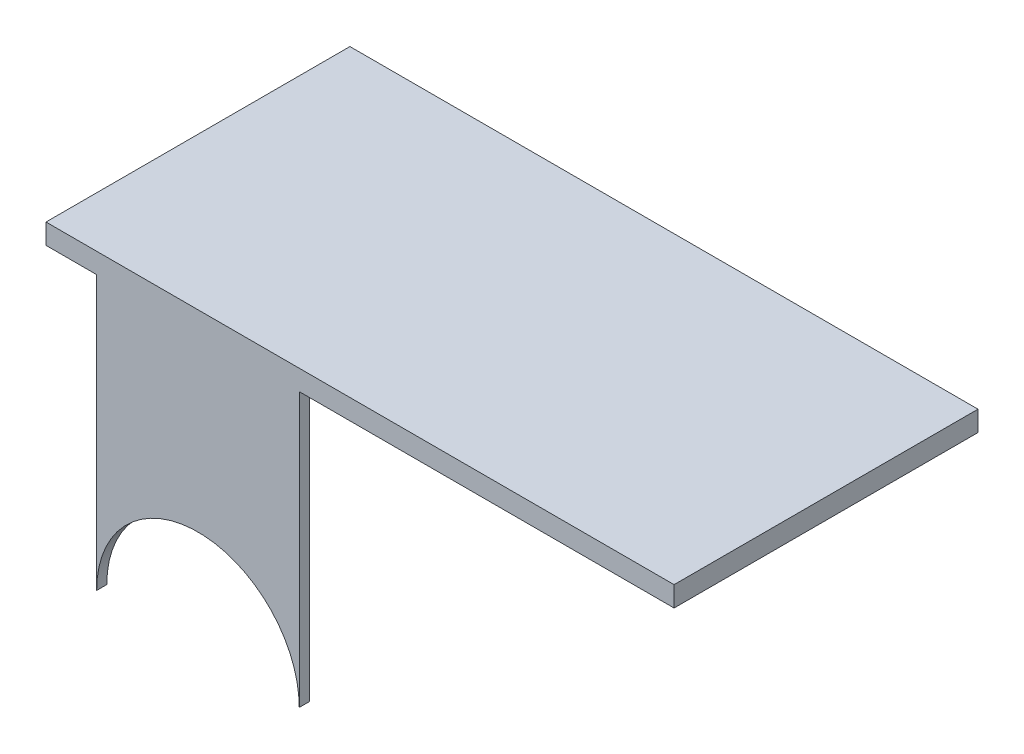
SolidWorks part; units mm, degrees
ref_plane "Front Plane" through (0, 0, 0) normal (0, 0, 1) x (1, 0, 0)
ref_plane "Top Plane" through (0, 0, 0) normal (0, 1, 0) x (1, 0, 0)
ref_plane "Right Plane" through (0, 0, 0) normal (1, 0, 0) x (0, 0, -1)
sketch "Sketch2" plane through (0, 0, 0) normal (0, 0, 1) x (1, 0, 0)
  line L0 (-44.925, -5.1312) -> (-44.925, 21.8688)
  line L1 (-44.925, 21.8688) -> (-24.925, 21.8688)
  line L2 (-24.925, 21.8688) -> (-24.925, -5.1312)
  arc A1 (-44.925, -5.1312) -> (-24.925, -5.1312) centre (-34.925, -5.1312) cw
  point P1 (0, 0)
  dimension "D1" = 10
  dimension "D2" = 27
  dimension "D3" = 27
  dimension "D4" = 20
extrude "Boss-Extrude1" add sketch "Sketch2" along normal blind 1
sketch "Sketch3" plane through (0, 21.8688, 0) normal (0, 1, 0) x (1, 0, 0)
  line L0 (-44.925, -1) -> (-49.925, -1)
  line L1 (-44.925, -1) -> (12.075, -1)
  line L3 (-49.925, 29) -> (12.075, 29)
  line L4 (12.075, -1) -> (12.075, 29)
  line L5 (-49.925, -1) -> (-49.925, 29)
  point P5 (-49.3413, 29)
  dimension "D1" = 5
  dimension "D2" = 30
  dimension "D3" = 62
extrude "Boss-Extrude2" add sketch "Sketch3" along normal blind 2
